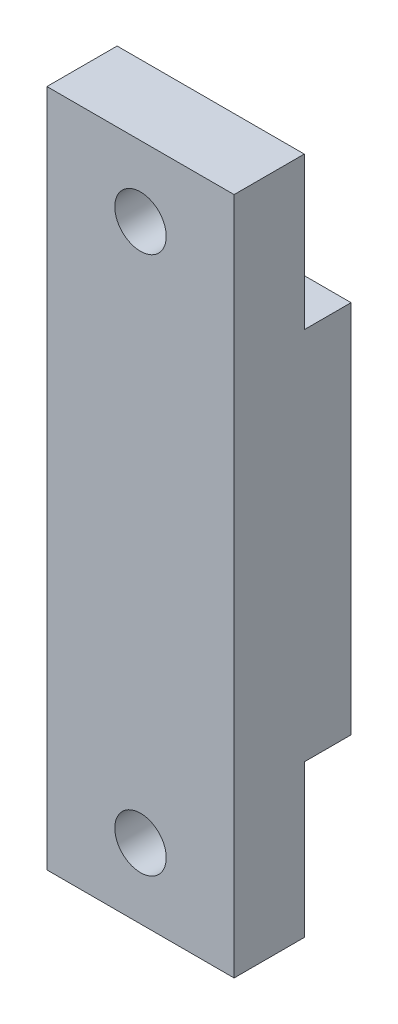
SolidWorks part; units mm, degrees
ref_plane "前视基准面" through (0, 0, 0) normal (0, 0, 1) x (1, 0, 0)
ref_plane "上视基准面" through (0, 0, 0) normal (0, 1, 0) x (1, 0, 0)
ref_plane "右视基准面" through (0, 0, 0) normal (1, 0, 0) x (0, 0, -1)
sketch "草图1" plane through (0, 0, 0) normal (0, 0, 1) x (1, 0, 0)
  line L1 (-4, 14.5) -> (4, 14.5)
  line L2 (-4, 14.5) -> (-4, -14.5)
  line L3 (-4, -14.5) -> (4, -14.5)
  line L4 (4, 14.5) -> (4, -14.5)
  line L5 (-4, 14.5) -> (4, -14.5) construction
  line L6 (-4, -14.5) -> (4, 14.5) construction
  point P0 (0, 0)
  dimension "D1" = 8
  dimension "D2" = 29
extrude "主体" add sketch "草图1" along normal blind 3
sketch "草图2" plane through (0, 0, 0) normal (0, 0, 1) x (1, 0, 0)
  line L0 (4, -14.5) -> (4, 14.5) construction
  line L1 (4, 8) -> (-4, 8)
  line L2 (4, 8) -> (4, -8)
  line L3 (4, -8) -> (-4, -8)
  line L4 (-4, 8) -> (-4, -8)
  line L5 (4, 8) -> (-4, -8) construction
  line L6 (4, -8) -> (-4, 8) construction
  point P0 (0, 0)
  dimension "D1" = 16
extrude "接线柱" add sketch "草图2" against normal blind 2
sketch "草图3" plane through (0, 0, 3) normal (0, 0, 1) x (1, 0, 0)
  line L0 (0, -3.905) -> (0, 3.905) construction
  line L1 (4, 14.5) -> (-4, 14.5) construction
  line L2 (3.905, 0) -> (-3.905, 0) construction
  circle A0 centre (0, 11.5) radius 1.1
  circle A1 centre (0, -11.5) radius 1.1
  dimension "D2" = 2.2
  dimension "D1" = 3
extrude "螺丝孔" cut sketch "草图3" against normal up to next
